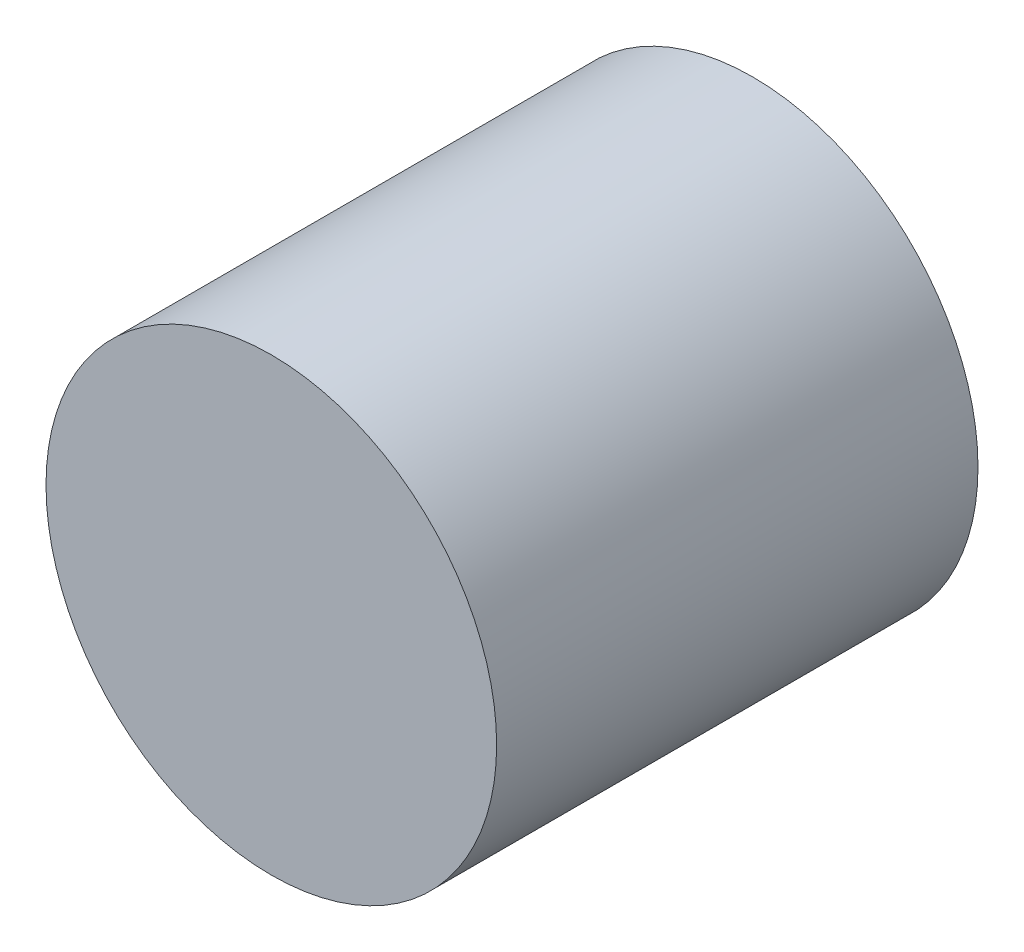
SolidWorks part; units mm, degrees
ref_plane "Front" through (0, 0, 0) normal (0, 0, 1) x (1, 0, 0)
ref_plane "Top" through (0, 0, 0) normal (0, 1, 0) x (1, 0, 0)
ref_plane "Right" through (0, 0, 0) normal (1, 0, 0) x (0, 0, -1)
sketch "Sketch1" plane through (0, 0, 0) normal (0, 0, 1) x (1, 0, 0)
  circle A0 centre (0, 0) radius 5.588
  dimension "D1" = 11.176
extrude "Boss-Extrude1" add sketch "Sketch1" along normal blind 11.938 contours A0
